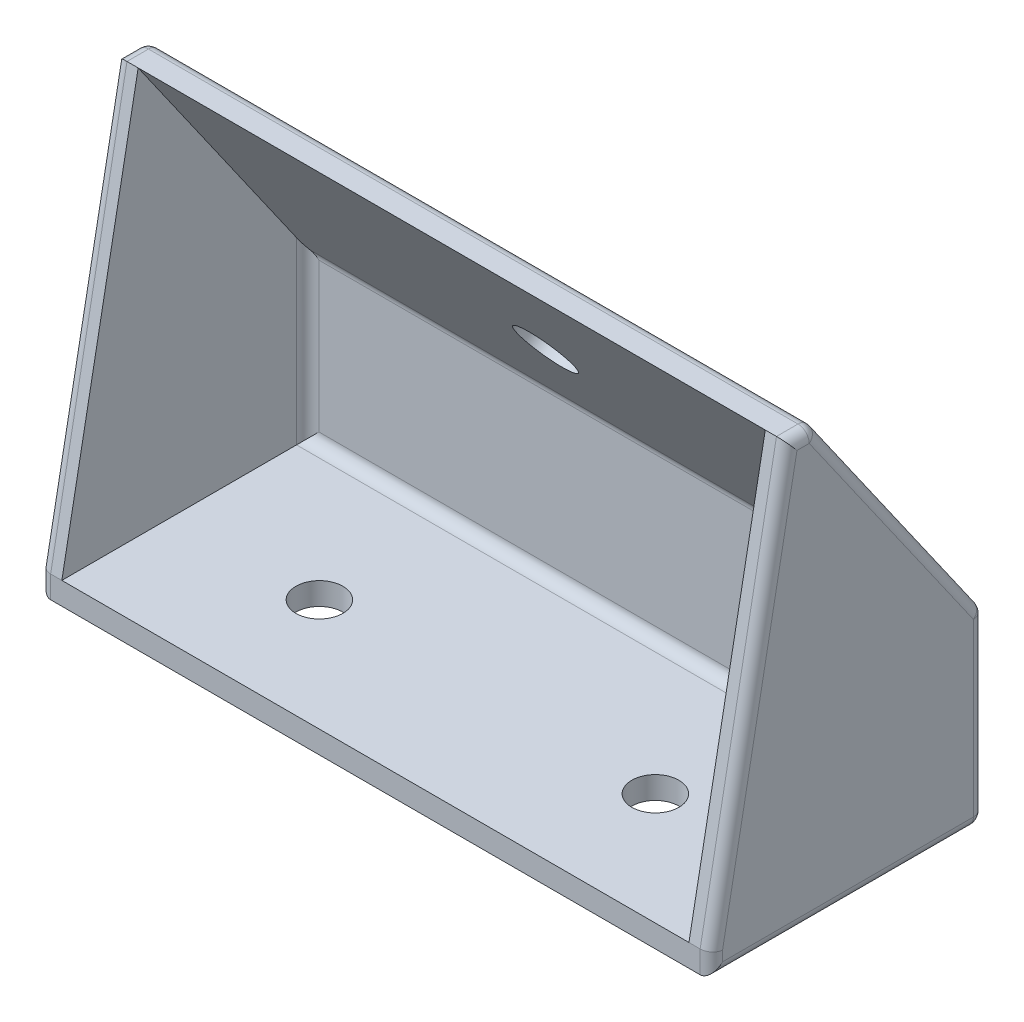
SolidWorks part; units mm, degrees
ref_plane "Front Plane" through (0, 0, 0) normal (0, 0, 1) x (1, 0, 0)
ref_plane "Top Plane" through (0, 0, 0) normal (0, 1, 0) x (1, 0, 0)
ref_plane "Right Plane" through (0, 0, 0) normal (1, 0, 0) x (0, 0, -1)
sketch "Sketch1" plane through (0, 0, 0) normal (1, 0, 0) x (0, 0, -1)
  line L0 (0, 0) -> (33.528, 0)
  line L1 (14.2971, 27.4645) -> (0, 27.4645)
  line L2 (0, 0) -> (0, 27.4645)
  line L3 (14.2971, 27.4645) -> (33.528, 0)
  dimension "D1" = 55
  dimension "D2" = 33.528
extrude "Boss-Extrude1" add sketch "Sketch1" along normal mid plane 76.2
sketch "Sketch5" plane through (0, 0, 0) normal (0, -1, 0) x (1, 0, 0)
  line L0 (-38.1, 0) -> (-38.1, -33.528) construction
  line L1 (38.1, 0) -> (-38.1, 0) construction
  line L2 (38.1, 0) -> (38.1, -33.528) construction
  line L3 (38.1, -33.528) -> (-38.1, -33.528) construction
  line L4 (-38.1, 0) -> (-38.1, -33.528)
  line L5 (38.1, 0) -> (-38.1, 0)
  line L6 (38.1, 0) -> (38.1, -33.528)
  line L7 (38.1, -33.528) -> (-38.1, -33.528)
extrude "Boss-Extrude2" add sketch "Sketch5" along normal blind 21.082
sketch "Sketch6" plane through (38.1, 0, 0) normal (1, 0, 0) x (0, 0, -1)
  line L0 (2.54, 39.8271) -> (2.54, -18.542)
  line L1 (2.54, -18.542) -> (30.4272, -18.542)
  line L2 (30.4272, -18.542) -> (30.4272, 0)
  line L3 (17.0434, 0) -> (-17.0434, 0) construction
  line L4 (30.4272, 0) -> (2.54, 39.8271)
  line L5 (33.528, 0) -> (14.2971, 27.4645) construction
  line L7 (0, 27.565) -> (0, -27.565) construction
  line L8 (33.528, -21.082) -> (0, -21.082) construction
  dimension "D1" = 2.54
  dimension "D2" = 2.54
  dimension "D3" = 2.54
extrude "Cut-Extrude2" cut sketch "Sketch6" against normal through all
sketch "Sketch7" plane through (0, -18.542, 0) normal (0, 1, 0) x (1, 0, 0)
  circle A2 centre (19.05, 15.24) radius 2.667
  circle A3 centre (-19.05, 15.24) radius 2.667
  dimension "D1" = 5.334
  dimension "D2" = 5.334
  dimension "D3" = 38.1
extrude "Cut-Extrude3" cut sketch "Sketch7" against normal through all
sketch "Sketch12" plane through (0, 15.753, -22.4976) normal (0, 0.5736, -0.8192) x (-1, 0, 0)
  line L0 (0, 14.2971) -> (0, -19.2309) construction
  line L1 (-38.1, 14.2971) -> (38.1, 14.2971) construction
  line L2 (-38.1, -19.2309) -> (38.1, -19.2309) construction
  circle A0 centre (0, -2.4669) radius 3.25
  dimension "D1" = 6.5
extrude "Cut-Extrude7" cut sketch "Sketch12" against normal up to surface (2.54 mm away) up to face at (0, 13.7323, -20.8118)
sketch "Sketch13" plane through (0, 0, 0) normal (0, 0, 1) x (1, 0, 0)
  line L1 (-40.2154, -22.2644) -> (39.7542, -22.2644)
  line L2 (-40.2154, -22.2644) -> (-40.2154, 29.9418)
  line L3 (-40.2154, 29.9418) -> (39.7542, 29.9418)
  line L4 (39.7542, -22.2644) -> (39.7542, 29.9418)
extrude "Cut-Extrude8" cut sketch "Sketch13" against normal up to surface (2.54 mm away) up to face at (0, 4.4613, -2.54)
sketch "Sketch16" plane through (38.1, 0, 0) normal (1, 0, 0) x (0, 0, -1)
  line L0 (2.54, -18.542) -> (30.4272, -18.542)
  line L1 (30.4272, -18.542) -> (30.4272, 0)
  line L2 (30.4272, 0) -> (11.1964, 27.4645)
  line L3 (11.1964, 27.4645) -> (2.54, -18.542)
extrude "Boss-Extrude4" add sketch "Sketch16" against normal blind 2.54
sketch "Sketch17" plane through (-38.1, 0, 0) normal (-1, 0, 0) x (0, 0, 1)
  line L0 (-11.1964, 27.4645) -> (-30.4272, 0)
  line L1 (17.0434, 0) -> (-17.0434, 0) construction
  line L2 (-30.4272, 0) -> (-11.1964, 27.4645) construction
  line L3 (-30.4272, 0) -> (-30.4272, -18.542)
  line L4 (-30.4272, -18.542) -> (-2.54, -18.542)
  line L5 (-2.54, -18.542) -> (-11.1964, 27.4645)
extrude "Boss-Extrude10" add sketch "Sketch17" against normal blind 2.54
fillet "Fillet8" radius 1.27 20 edges at (35.56, -9.271, -30.4272) (0, -18.542, -30.4272) (-35.56, -9.271, -30.4272) (0, 0, -30.4272) (38.1, -21.082, -18.034) (38.1, -19.812, -2.54) (38.1, 4.4613, -6.8682) (38.1, 27.4645, -12.7467) (0, -21.082, -33.528) (38.1, -10.541, -33.528) (-38.1, -21.082, -18.034) (-38.1, -10.541, -33.528) (-38.1, 27.4645, -12.7467) (-38.1, 4.4613, -6.8682) (-38.1, -19.812, -2.54) (0, 0, -33.528) (38.1, 13.7323, -23.9126) (0, 27.4645, -14.2971) (-38.1, 13.7323, -23.9126) (0, 16.3945, -22.0484)
